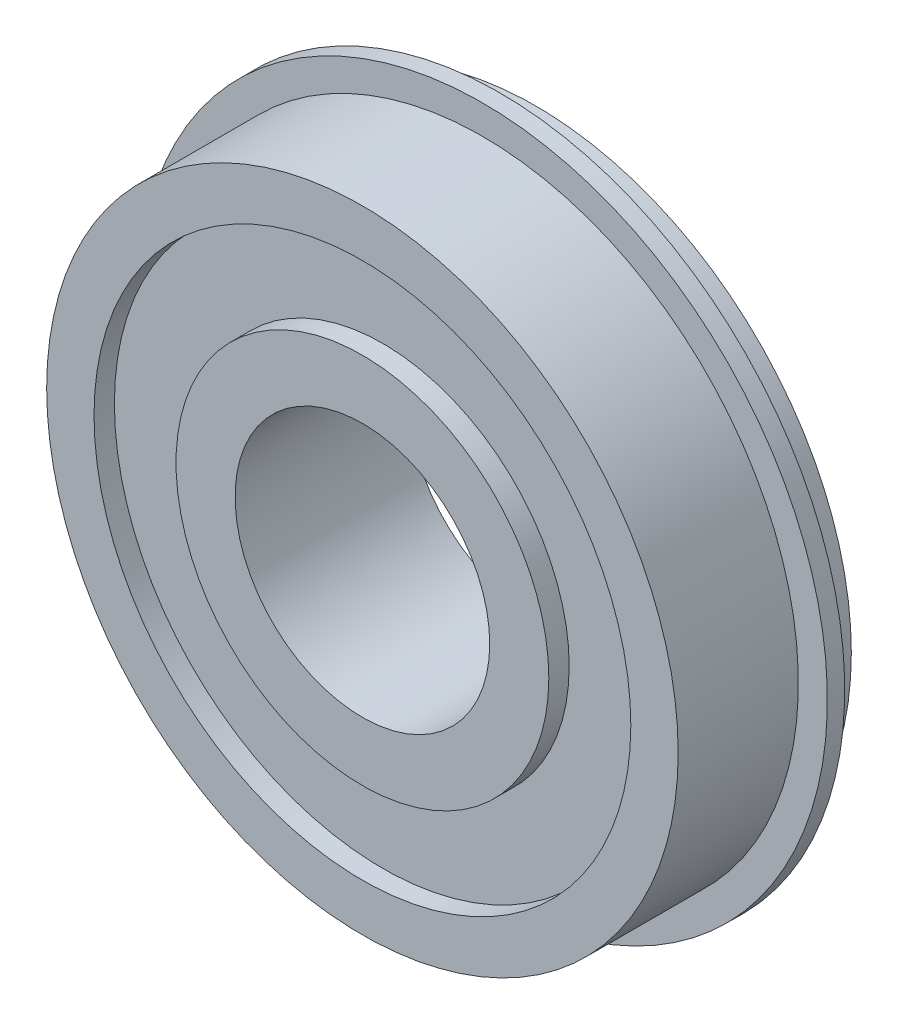
SolidWorks part; units mm, degrees
ref_plane "Front Plane" through (0, 0, 0) normal (0, 0, 1) x (1, 0, 0)
ref_plane "Top Plane" through (0, 0, 0) normal (0, 1, 0) x (1, 0, 0)
ref_plane "Right Plane" through (0, 0, 0) normal (1, 0, 0) x (0, 0, -1)
sketch "Sketch1" plane through (0, 0, 0) normal (0, 0, 1) x (1, 0, 0)
  circle A0 centre (0, 0) radius 31
  circle A1 centre (0, 0) radius 12.5
  dimension "D1" = 62
  dimension "D2" = 25
extrude "Boss-Extrude1" add sketch "Sketch1" along normal mid plane 17
sketch "Sketch3" plane through (0, 0, 8.5) normal (0, 0, 1) x (1, 0, 0)
  circle A0 centre (0, 0) radius 18.3
  circle A1 centre (0, 0) radius 26.35
  dimension "D1" = 36.6
  dimension "D2" = 52.7
extrude "Cut-Extrude1" cut sketch "Sketch3" against normal blind 2
mirror "Mirror1" about plane through (0, 0, 0) normal (0, 0, 1) of "Cut-Extrude1"
ref_plane "Plane1" through (0, 0, -5) normal (0, 0, -1) x (-1, 0, 0)
sketch "Sketch4" plane through (0, 0, -5) normal (0, 0, -1) x (-1, 0, 0)
  circle A0 centre (0, 0) radius 33.85
  circle A1 centre (0, 0) radius 31 construction
  circle A2 centre (0, 0) radius 31
  dimension "D1" = 67.7
extrude "Boss-Extrude2" add sketch "Sketch4" against normal blind 1.7
